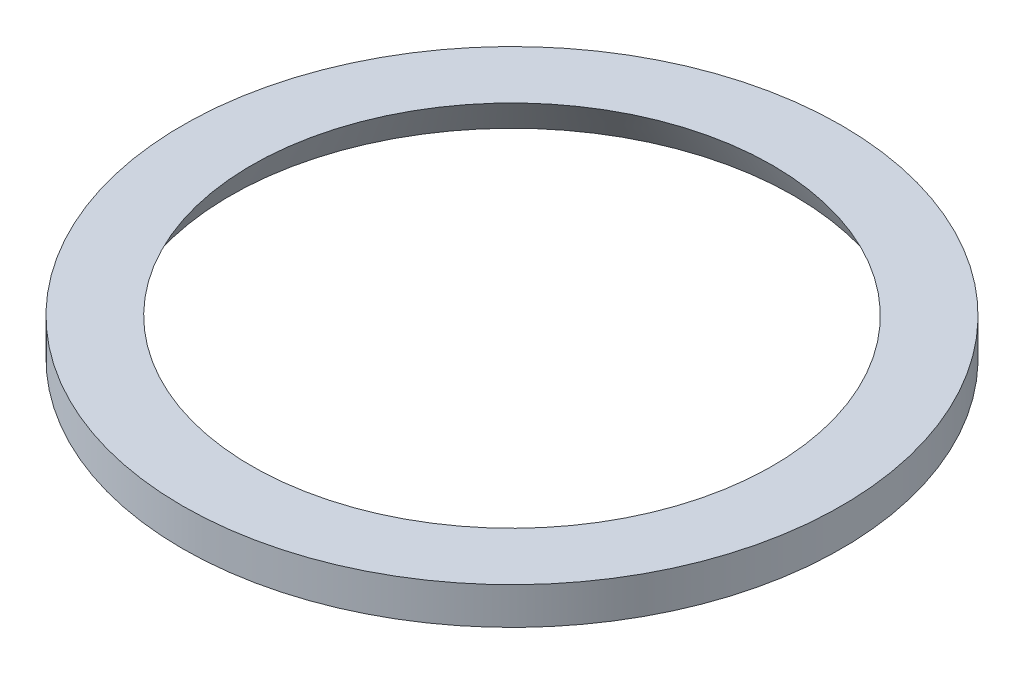
SolidWorks part; units mm, degrees
ref_plane "Front Plane" through (0, 0, 0) normal (0, 0, 1) x (1, 0, 0)
ref_plane "Top Plane" through (0, 0, 0) normal (0, 1, 0) x (1, 0, 0)
ref_plane "Right Plane" through (0, 0, 0) normal (1, 0, 0) x (0, 0, -1)
sketch "Sketch2" plane through (0, 0, 0) normal (0, 0, 1) x (1, 0, 0)
  line L0 (0, 0) -> (-89, 0) construction
  line L1 (-89, 0) -> (-89, 10)
  line L2 (-89, 0) -> (-76.1132, 0)
  line L3 (-76.1132, 0) -> (-70.3397, 10)
  line L4 (-89, 10) -> (-70.3397, 10)
  line L5 (0, 0) -> (0, 8.4703) construction
  line L6 (-70.3397, 10) -> (-79, -5) construction
  point P8 (-72.0382, 10)
  point P9 (-72.6801, 10)
  dimension "D1" = 89
  dimension "D2" = 10
  dimension "D3" = 10
  dimension "D4" = 60
  dimension "D5" = 5
revolve "Revolve1" add sketch "Sketch2" angle 360 about L5
